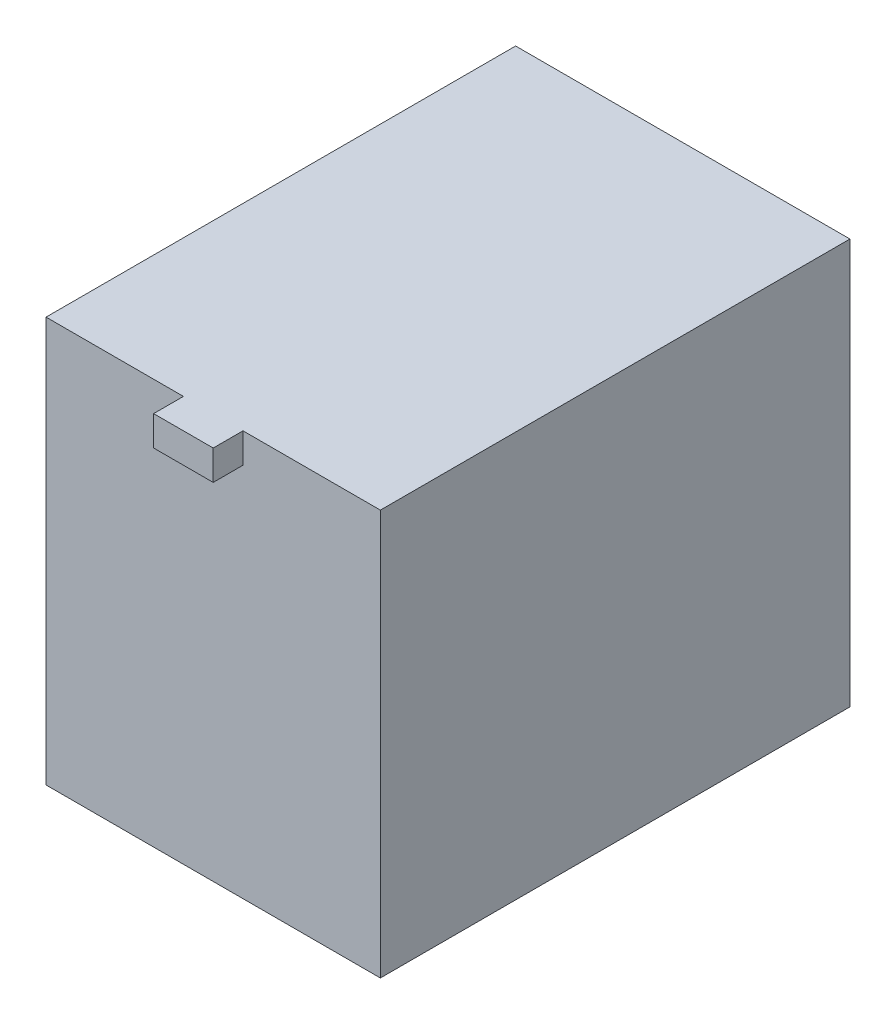
SolidWorks part; units mm, degrees
ref_plane "前视基准面" through (0, 0, 0) normal (0, 0, 1) x (1, 0, 0)
ref_plane "上视基准面" through (0, 0, 0) normal (0, 1, 0) x (1, 0, 0)
ref_plane "右视基准面" through (0, 0, 0) normal (1, 0, 0) x (0, 0, -1)
other "Configuration Table"
sketch "草图1" plane through (0, 0, 0) normal (0, 1, 0) x (1, 0, 0)
  line L1 (-28.05, -39.4) -> (28.05, -39.4)
  line L2 (-28.05, -39.4) -> (-28.05, 39.4)
  line L3 (-28.05, 39.4) -> (28.05, 39.4)
  line L4 (28.05, -39.4) -> (28.05, 39.4)
  line L5 (-28.05, -39.4) -> (28.05, 39.4) construction
  line L6 (-28.05, 39.4) -> (28.05, -39.4) construction
  point P0 (0, 0)
  point P7 (0, 0)
  dimension "D1" = 56.1
  dimension "D2" = 78.8
extrude "凸台-拉伸1" add sketch "草图1" along normal blind 68
sketch "草图2" plane through (0, 0, 39.4) normal (0, 0, 1) x (1, 0, 0)
  line L0 (-5, 68) -> (5, 68)
  line L1 (-28.05, 68) -> (28.05, 68) construction
  line L2 (5, 68) -> (5, 63)
  line L3 (5, 63) -> (-5, 63)
  line L4 (0, 63) -> (0, 68)
  line L5 (0, 0) -> (0, 81.5841) construction
  line L6 (-5, 68) -> (-5, 63)
  line M8 (28.05, 68) -> (-28.05, 68)
  dimension "D1" = 5
  dimension "D2" = 5
extrude "凸台-拉伸2" add sketch "草图2" along normal blind 5 contours L0 L6 L3 L4 | L4 L3 L2 M8
